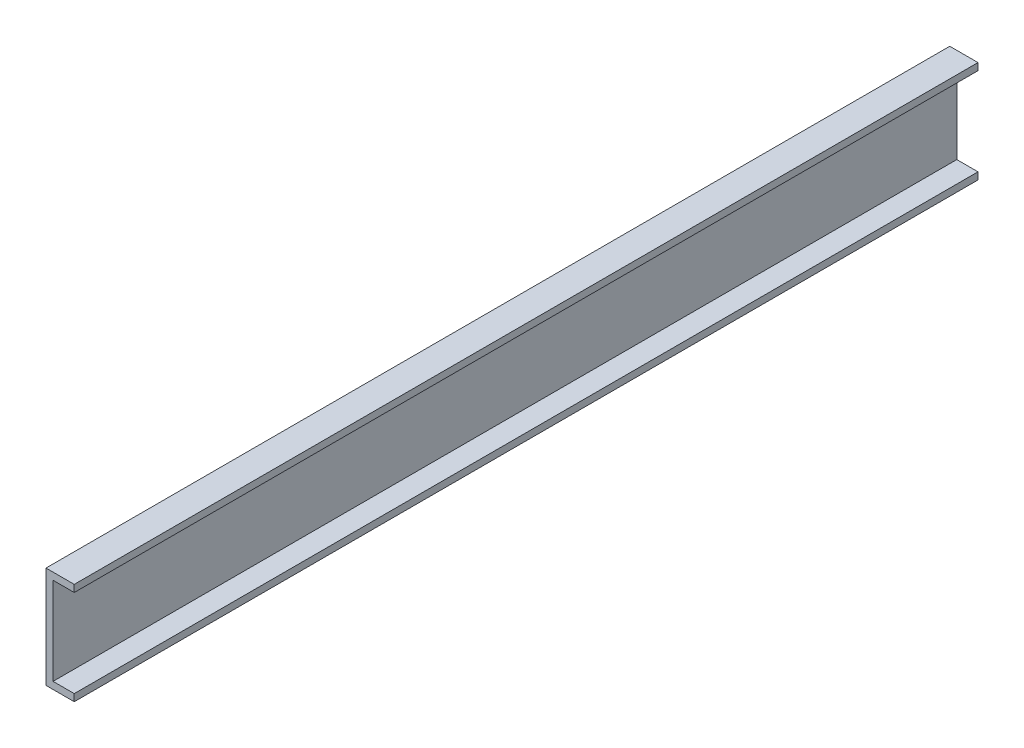
SolidWorks part; units mm, degrees
material "Chrome Stainless Steel"
ref_plane "Front Plane" through (0, 0, 0) normal (0, 0, 1) x (1, 0, 0)
ref_plane "Top Plane" through (0, 0, 0) normal (0, 1, 0) x (1, 0, 0)
ref_plane "Right Plane" through (0, 0, 0) normal (1, 0, 0) x (0, 0, -1)
sketch "Sketch1" plane through (0, 0, 0) normal (1, 0, 0) x (0, 0, -1)
  line L1 (0, 0) -> (406.4, 0)
  line L2 (0, 0) -> (0, 45.72)
  line L3 (0, 45.72) -> (406.4, 45.72)
  line L4 (406.4, 0) -> (406.4, 45.72)
  dimension "D1" = 406.4
  dimension "D2" = 45.72
extrude "Boss-Extrude1" add sketch "Sketch1" along normal blind 12.7
sketch "Sketch2" plane through (0, 0, 0) normal (0, 0, 1) x (1, 0, 0)
  line L0 (12.7, 45.72) -> (12.7, 0) construction
  line L1 (12.7, 42.545) -> (3.175, 42.545)
  line L2 (12.7, 42.545) -> (12.7, 3.175)
  line L3 (12.7, 3.175) -> (3.175, 3.175)
  line L4 (3.175, 42.545) -> (3.175, 3.175)
  line L5 (12.7, 45.72) -> (0, 45.72) construction
  dimension "D1" = 9.525
  dimension "D2" = 39.37
  dimension "D3" = 3.175
extrude "Cut-Extrude1" cut sketch "Sketch2" against normal through all
